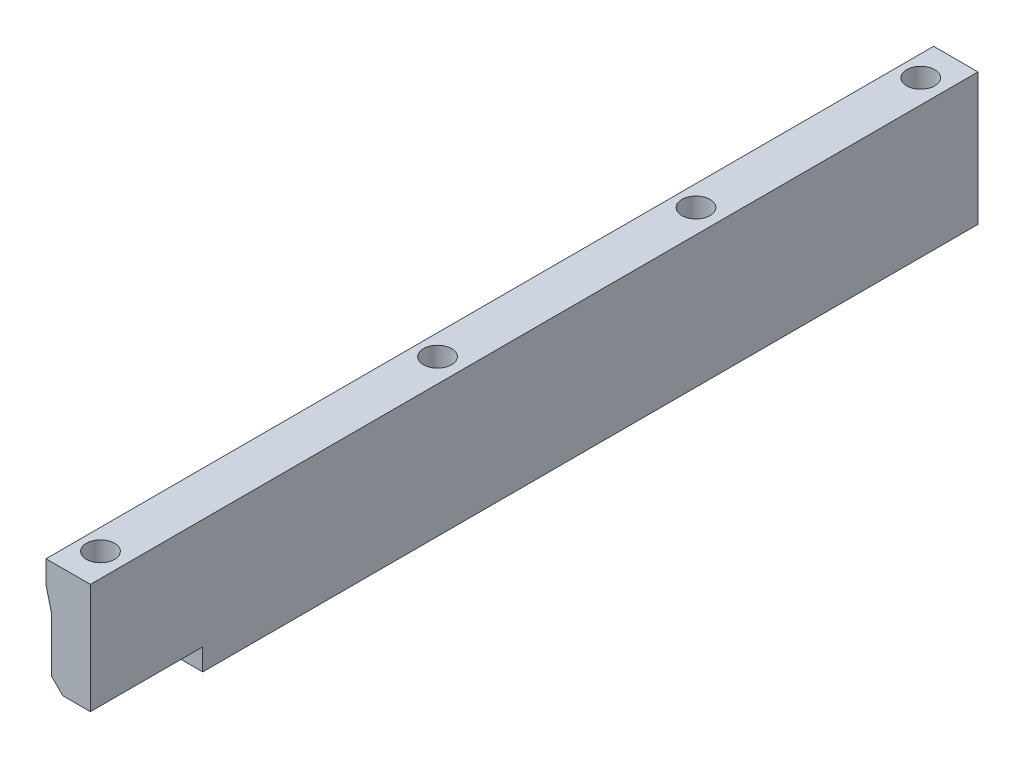
SolidWorks part; units mm, degrees
ref_plane "Front Plane" through (0, 0, 0) normal (0, 0, 1) x (1, 0, 0)
ref_plane "Top Plane" through (0, 0, 0) normal (0, 1, 0) x (1, 0, 0)
ref_plane "Right Plane" through (0, 0, 0) normal (1, 0, 0) x (0, 0, -1)
sketch "Sketch1" plane through (0, 0, 0) normal (0, 0, 1) x (1, 0, 0)
  line L0 (-49, 0) -> (49, 0) construction
  line L1 (-48.6, -2.25) -> (-48.6, 2.25)
  line L2 (-38.5, 0) -> (38.5, 0) construction
  line L3 (-38.5, 0) -> (-38.5, 33.8173) construction
  line L4 (-38.5, 33.8173) -> (38.5, 33.8173) construction
  line L5 (38.5, 0) -> (38.5, 33.8173) construction
  line L6 (-48.6, 2.25) -> (-45.4, 2.25)
  line L7 (-45.4, 2.25) -> (-45.4, 6.25)
  line L8 (-45.4, 14.25) -> (-38.5, 14.25)
  line L9 (-38.5, 14.25) -> (-38.5, -9.25)
  line L10 (-38.5, -9.25) -> (-45.4, -9.25)
  line L11 (-45.4, -9.25) -> (-45.4, -2.25)
  line L12 (-45.4, -2.25) -> (-48.6, -2.25)
  line L13 (-45.4, 14.25) -> (-46.4, 14.25)
  line L15 (-46.4, 14.25) -> (-46.4, 10.25)
  line L16 (-46.4, 10.25) -> (-45.4, 6.25)
  point P2 (0, 0)
  point P11 (-48.6, 0)
  dimension "D1" = 98
  dimension "D2" = 77
  dimension "D3" = 4.5
  dimension "D4" = 3.2
  dimension "D5" = 0.4
  dimension "D6" = 12
  dimension "D7" = 7
  dimension "D8" = 1
  dimension "D9" = 8
  dimension "D10" = 4
extrude "Boss-Extrude1" add sketch "Sketch1" against normal blind 138
sketch "Sketch2" plane through (0, 0, 0) normal (0, 0, 1) x (1, 0, 0)
  line L0 (-45.4, -2.25) -> (-45.4, -9.25) construction
  line L1 (-38.5, 14.25) -> (-44.4, 14.25)
  line L2 (-38.5, 14.25) -> (-38.5, -5.3765)
  line L3 (-38.5, -5.3765) -> (-45.4, -5.3765)
  line L4 (-45.4, 6.25) -> (-45.4, -5.3765)
  line L5 (-38.5, 14.25) -> (-46.4, 14.25) construction
  line L7 (-38.5, 14.25) -> (-46.4, 14.25)
  line L8 (-46.4, 10.25) -> (-45.4, 6.25) construction
  line L9 (-46.4, 14.25) -> (-46.4, 10.25) construction
  line L10 (-46.4, 10.25) -> (-45.4, 6.25)
  line L11 (-46.4, 14.25) -> (-46.4, 10.25)
  line L12 (-38.5, -9.25) -> (-38.5, 14.25) construction
  line L14 (-38.5, -5.3765) -> (-38.5, 14.25)
extrude "Boss-Extrude2" add sketch "Sketch2" along normal blind 20
sketch "Sketch4" plane through (0, 14.25, 0) normal (0, 1, 0) x (1, 0, 0)
  line L0 (-42.7, -20) -> (-42.7, 138) construction
  line L1 (-38.5, -20) -> (-46.4, -20) construction
  line L2 (-38.5, 138) -> (-46.4, 138) construction
  line L4 (-46.4, 138) -> (-46.4, -20) construction
  point P8 (-42.7, 132)
  point P9 (-42.7, 92)
  point P10 (-42.7, 46)
  point P11 (-42.7, -14)
  dimension "D1" = 3.7
  dimension "D2" = 6
  dimension "D3" = 46
  dimension "D4" = 6
  dimension "D5" = 40
hole_wizard "CBORE for M5 Hex Head Bolt1" positions "3DSketch2" profile "Sketch5" counterbore size "M5" standard "DIN"
sketch3d "3DSketch2"
  point P0 (-42.7, 14.25, -132)
  point P3 (-42.7, 14.25, -92)
  point P6 (-42.7, 14.25, -46)
  point P9 (-42.7, 14.25, 14)
sketch "Sketch5" plane through (-42.7, 14.25, -132) normal (1, 0, 0) x (0, 0, 1)
  line L0 (0, 0) -> (0, 15)
  line L1 (0, 15) -> (1.6, 15)
  line L2 (1.6, 15) -> (1.6, 5)
  line L3 (1.6, 5) -> (2.5, 5)
  line L4 (2.5, 5) -> (2.5, 0)
  line L5 (2.5, 0) -> (0, 0)
  line L10 (0, 15) -> (-1.6, 15) construction
  line L11 (0, -6.35) -> (0, 107.95) construction
  dimension "Hole Dia." = 3.2
  dimension "Hole Depth" = 15
  dimension "C'Bore Dia." = 5
  dimension "C'Bore Depth" = 5
  dimension "Drill Angle" = 180
chamfer "Chamfer1" distance 2 angle 45 2 edges at (-45.4, -9.25, -69) (-45.4, -5.3765, 10)
